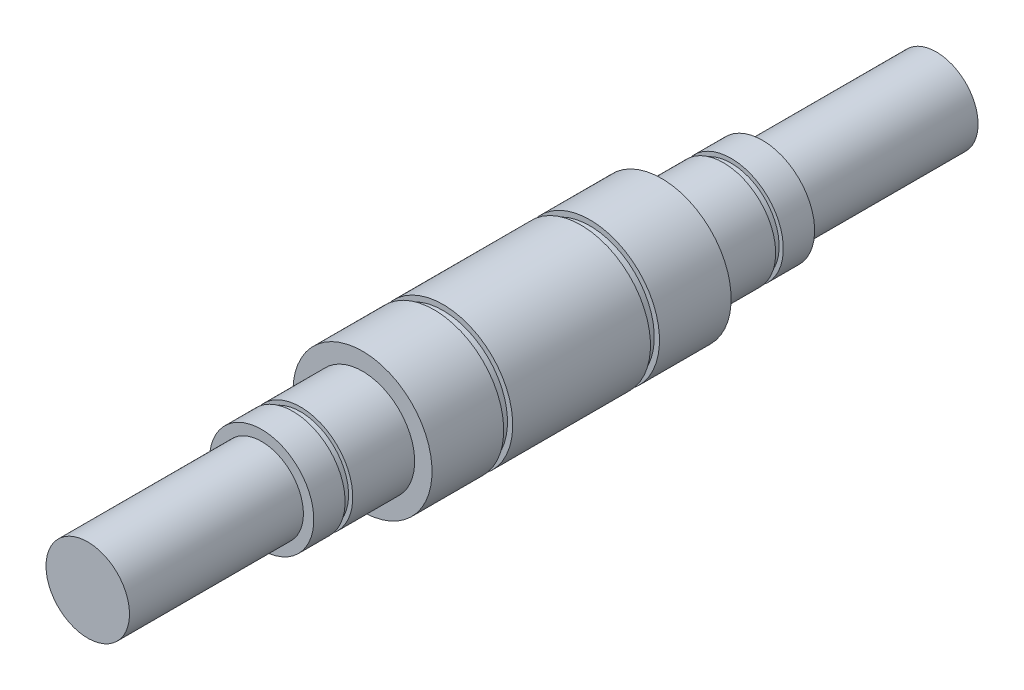
SolidWorks part; units mm, degrees
ref_plane "Front Plane" through (0, 0, 0) normal (0, 0, 1) x (1, 0, 0)
ref_plane "Top Plane" through (0, 0, 0) normal (0, 1, 0) x (1, 0, 0)
ref_plane "Right Plane" through (0, 0, 0) normal (1, 0, 0) x (0, 0, -1)
sketch "Sketch1" plane through (0, 0, 0) normal (0, 0, 1) x (1, 0, 0)
  circle A0 centre (0, 0) radius 10
  dimension "D1" = 20
extrude "Boss-Extrude1" add sketch "Sketch1" along normal mid plane 122
ref_axis "Axis1" through (0, 0, -67.1) along (0, 0, 1)
sketch "Sketch2" plane through (0, 0, 0) normal (1, 0, 0) x (0, 0, -1)
  line L0 (61, 10) -> (-61, 10) construction
  line L1 (21.5, 10) -> (61, 10)
  line L2 (21.5, 10) -> (21.5, 7.5)
  line L3 (21.5, 7.5) -> (61, 7.5)
  line L4 (61, 10) -> (61, 7.5)
  line L5 (61, -10) -> (61, 10) construction
  line L6 (67.1, 0) -> (-67.1, 0) construction
  dimension "D1" = 21.5
  dimension "D2" = 7.5
revolve "Cut-Revolve1" cut sketch "Sketch2" angle 360 about axis through (0, 0, -67.1) along (0, 0, 1)
mirror "Mirror1" about plane through (0, 0, 0) normal (0, 0, 1) of "Cut-Revolve1"
sketch "Sketch3" plane through (0, 0, 0) normal (1, 0, 0) x (0, 0, -1)
  line L0 (61, 7.5) -> (21.5, 7.5) construction
  line L1 (36, 7.5) -> (61, 7.5)
  line L2 (36, 7.5) -> (36, 6)
  line L3 (36, 6) -> (61, 6)
  line L4 (61, 7.5) -> (61, 6)
  line L5 (61, -7.5) -> (61, 7.5) construction
  line L6 (67.1, 0) -> (-67.1, 0) construction
  dimension "D1" = 25
  dimension "D2" = 6
revolve "Cut-Revolve2" cut sketch "Sketch3" angle 360 about axis through (0, 0, -67.1) along (0, 0, 1)
mirror "Mirror2" about plane through (0, 0, 0) normal (0, 0, 1) of "Cut-Revolve2"
sketch "Sketch4" plane through (0, 0, 0) normal (1, 0, 0) x (0, 0, -1)
  line L0 (36, 7.5) -> (21.5, 7.5) construction
  line L1 (30.4, 7.5) -> (31.5, 7.5)
  line L2 (30.4, 7.5) -> (30.4, 6.9)
  line L3 (30.4, 6.9) -> (31.5, 6.9)
  line L4 (31.5, 7.5) -> (31.5, 6.9)
  line L5 (21.5, -10) -> (21.5, 10) construction
  line L6 (67.1, 0) -> (-67.1, 0) construction
  dimension "D1" = 10
  dimension "D2" = 1.1
  dimension "D3" = 6.9
revolve "Cut-Revolve3" cut sketch "Sketch4" angle 360 about axis through (0, 0, -67.1) along (0, 0, 1)
mirror "Mirror3" about plane through (0, 0, 0) normal (0, 0, 1) of "Cut-Revolve3"
sketch "Sketch5" plane through (0, 0, 0) normal (1, 0, 0) x (0, 0, -1)
  line L0 (21.5, 10) -> (-21.5, 10) construction
  line L1 (9.9, 10) -> (11.2, 10)
  line L2 (9.9, 10) -> (9.9, 9.25)
  line L3 (9.9, 9.25) -> (11.2, 9.25)
  line L4 (11.2, 10) -> (11.2, 9.25)
  line L5 (67.1, 0) -> (-67.1, 0) construction
  dimension "D1" = 11.2
  dimension "D2" = 1.3
  dimension "D3" = 9.25
revolve "Cut-Revolve4" cut sketch "Sketch5" angle 360 about axis through (0, 0, -67.1) along (0, 0, 1)
mirror "Mirror4" about plane through (0, 0, 0) normal (0, 0, 1) of "Cut-Revolve4"
